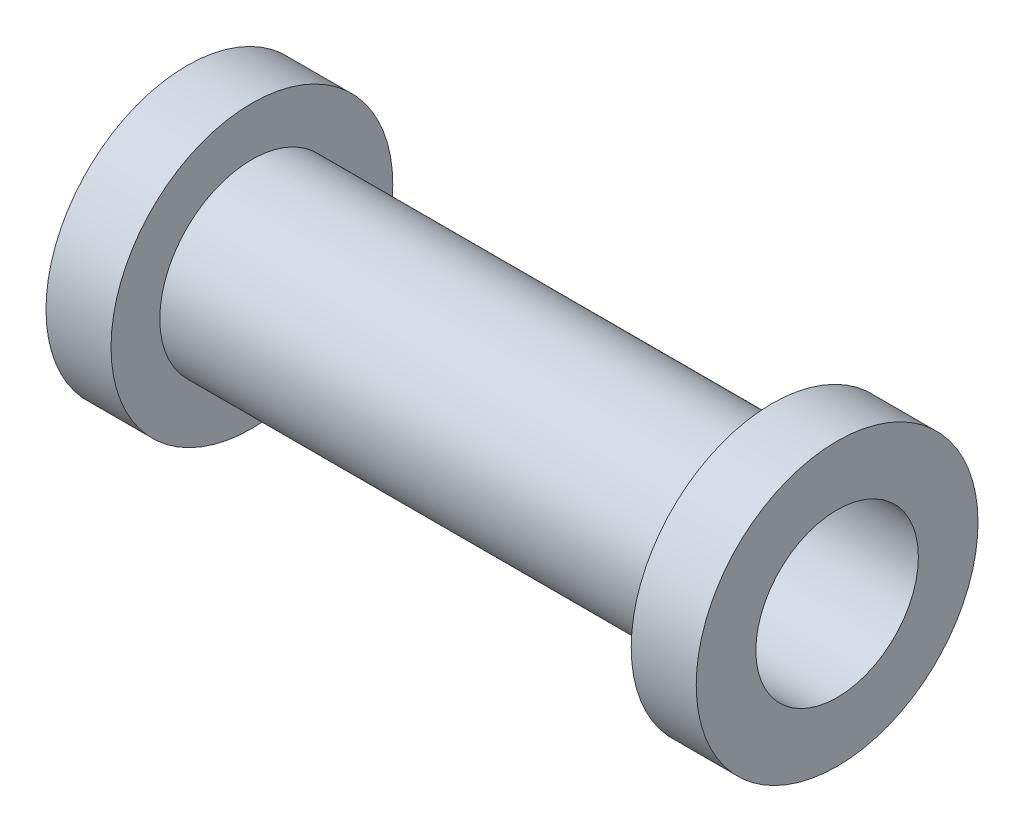
SolidWorks part; units mm, degrees
ref_plane "Front Plane" through (0, 0, 0) normal (0, 0, 1) x (1, 0, 0)
ref_plane "Top Plane" through (0, 0, 0) normal (0, 1, 0) x (1, 0, 0)
ref_plane "Right Plane" through (0, 0, 0) normal (1, 0, 0) x (0, 0, -1)
sketch "Sketch1" plane through (0, 0, 0) normal (0, 0, 1) x (1, 0, 0)
  line L0 (-30.48, 0) -> (30.48, 0) construction
  line L1 (30.48, 0) -> (30.48, 16.51)
  line L2 (30.48, 16.51) -> (38.1, 16.51)
  line L3 (38.1, 16.51) -> (38.1, 0)
  line L4 (38.1, 0) -> (30.48, 0)
  line L5 (30.48, 9.525) -> (-30.48, 9.525)
  line L6 (0, 9.525) -> (0, 10.795)
  line L7 (-30.48, 10.795) -> (30.48, 10.795)
  line L8 (0, 10.795) -> (0, 0) construction
  line L9 (-38.1, 0) -> (-30.48, 0)
  line L10 (-38.1, 16.51) -> (-38.1, 0)
  line L11 (-30.48, 16.51) -> (-38.1, 16.51)
  line L12 (-30.48, 0) -> (-30.48, 16.51)
  line L13 (30.48, 9.525) -> (38.1, 9.525)
  line L14 (-30.48, 9.525) -> (-38.1, 9.525)
  dimension "D1" = 7.62
  dimension "D2" = 9.525
  dimension "D3" = 38.1
  dimension "D4" = 1.27
  dimension "D5" = 16.51
revolve "Revolve2" add sketch "Sketch1" angle 360 about L0
